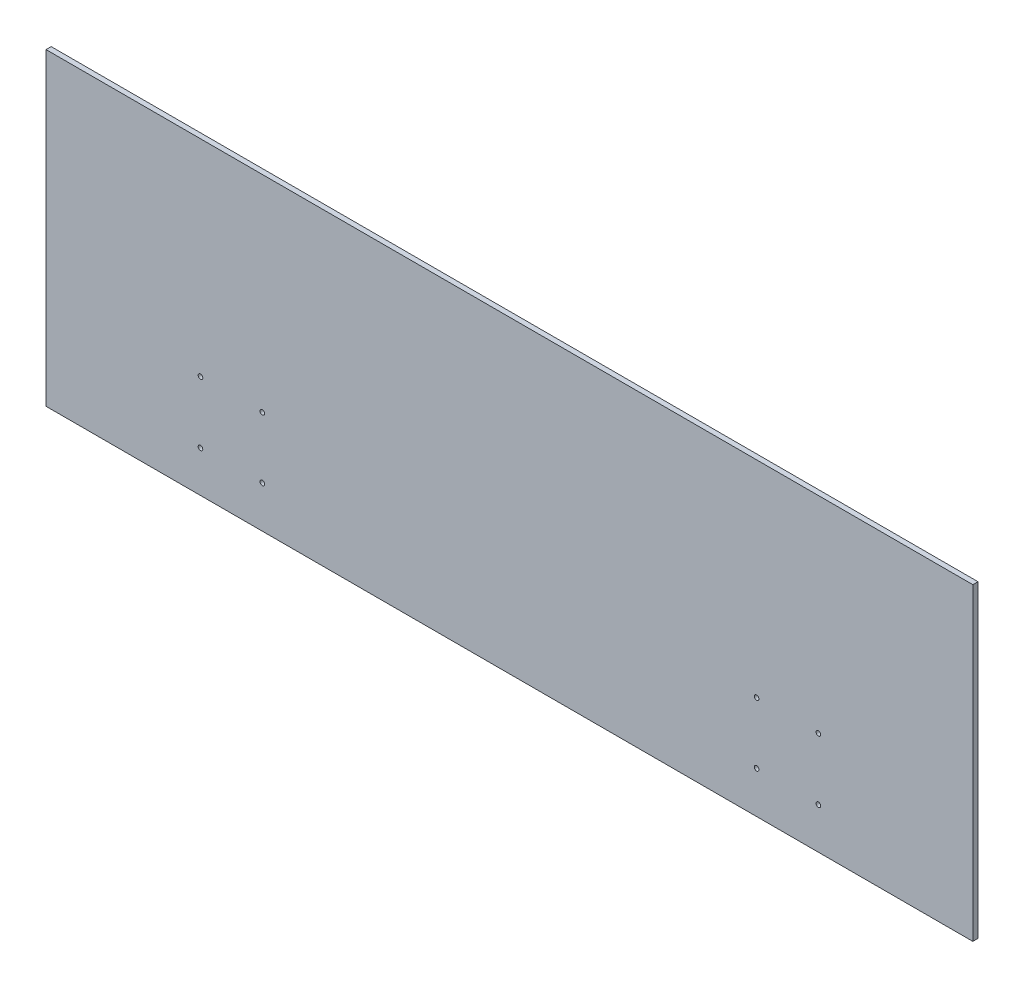
SolidWorks part; units mm, degrees
ref_plane "Front Plane" through (0, 0, 0) normal (0, 0, 1) x (1, 0, 0)
ref_plane "Top Plane" through (0, 0, 0) normal (0, 1, 0) x (1, 0, 0)
ref_plane "Right Plane" through (0, 0, 0) normal (1, 0, 0) x (0, 0, -1)
sketch "Sketch1" plane through (0, 0, 0) normal (0, 0, 1) x (1, 0, 0)
  line L0 (153.7367, -107.0285) -> (153.7367, -66.4591) construction
  line L1 (-296.2633, 192.9715) -> (603.7367, 192.9715)
  line L2 (-296.2633, 192.9715) -> (-296.2633, -107.0285)
  line L3 (-296.2633, -107.0285) -> (603.7367, -107.0285)
  line L4 (603.7367, 192.9715) -> (603.7367, -107.0285)
  circle A0 centre (-146.2633, -7.0285) radius 2.25
  circle A1 centre (-86.2633, -7.0285) radius 2.25
  circle A2 centre (-86.2633, -66.4591) radius 2.25
  circle A3 centre (-146.2633, -67.0285) radius 2.25
  circle A4 centre (453.7367, -67.0285) radius 2.25
  circle A5 centre (393.7367, -66.4591) radius 2.25
  circle A6 centre (393.7367, -7.0285) radius 2.25
  circle A7 centre (453.7367, -7.0285) radius 2.25
  dimension "D3" = 150
  dimension "D1" = 900
  dimension "D2" = 300
  dimension "D4" = 60
  dimension "D5" = 40
  dimension "D6" = 150
  dimension "D7" = 60
  dimension "D8" = 60
extrude "Boss-Extrude1" add sketch "Sketch1" along normal blind 5
